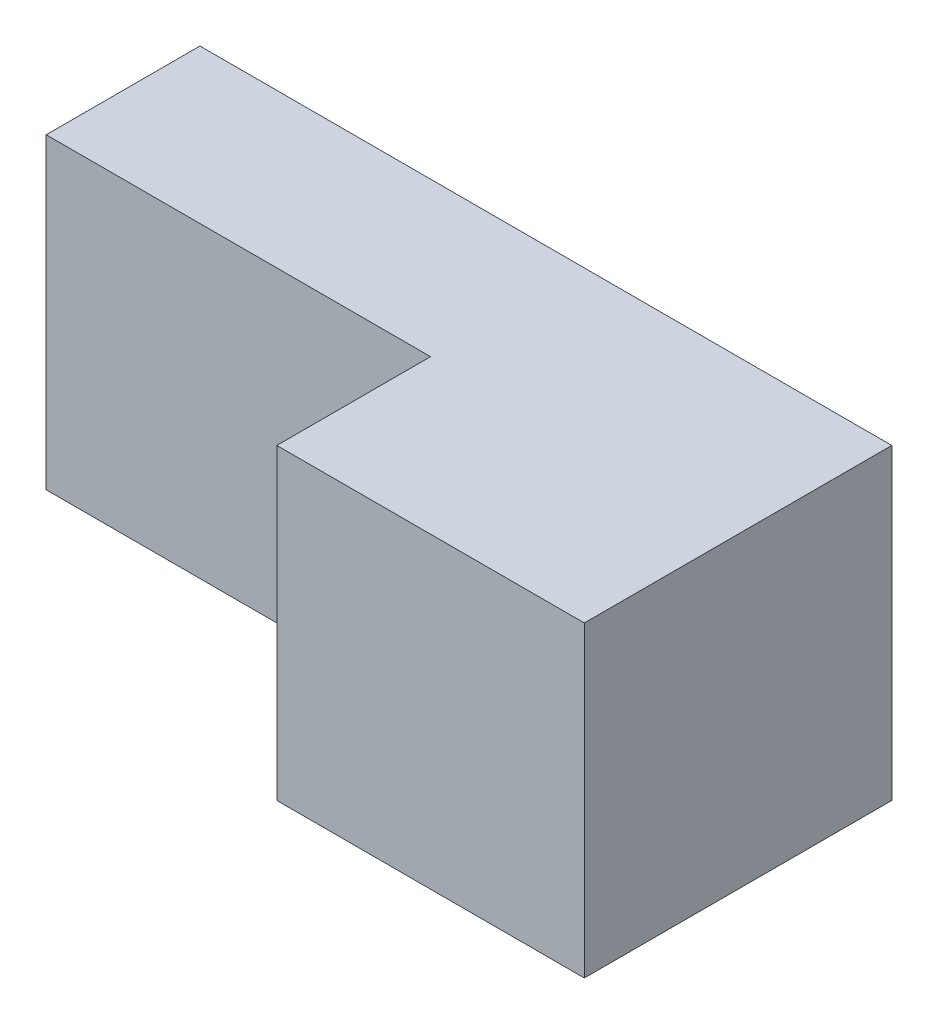
SolidWorks part; units mm, degrees
ref_plane "Front Plane" through (0, 0, 0) normal (0, 0, 1) x (1, 0, 0)
ref_plane "Top Plane" through (0, 0, 0) normal (0, 1, 0) x (1, 0, 0)
ref_plane "Right Plane" through (0, 0, 0) normal (1, 0, 0) x (0, 0, -1)
sketch "Sketch1" plane through (0, 0, 0) normal (0, 0, 1) x (1, 0, 0)
  line L1 (0, 0) -> (114.3, 0)
  line L2 (0, 0) -> (0, 50.8)
  line L3 (0, 50.8) -> (114.3, 50.8)
  line L4 (114.3, 0) -> (114.3, 50.8)
  dimension "D1" = 114.3
  dimension "D2" = 50.8
extrude "Boss-Extrude1" add sketch "Sketch1" along normal blind 25.4
sketch "Sketch2" plane through (0, 0, 25.4) normal (0, 0, 1) x (1, 0, 0)
  line L0 (0, 0) -> (114.3, 0) construction
  line L1 (114.3, 50.8) -> (63.5, 50.8)
  line L2 (114.3, 50.8) -> (114.3, 0)
  line L3 (114.3, 0) -> (63.5, 0)
  line L4 (63.5, 50.8) -> (63.5, 0)
  dimension "D1" = 50.8
extrude "Boss-Extrude2" add sketch "Sketch2" along normal blind 25.4
